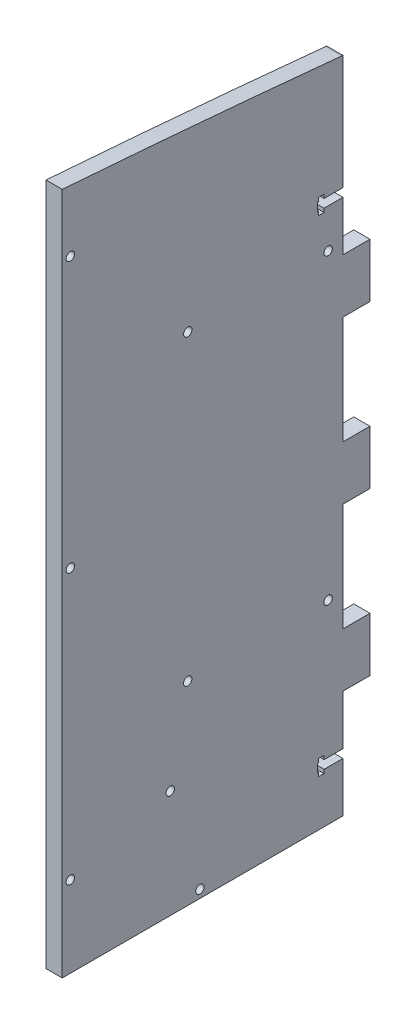
SolidWorks part; units mm, degrees
ref_plane "Płaszczyzna przednia" through (0, 0, 0) normal (0, 0, 1) x (1, 0, 0)
ref_plane "Płaszczyzna górna" through (0, 0, 0) normal (0, 1, 0) x (1, 0, 0)
ref_plane "Płaszczyzna prawa" through (0, 0, 0) normal (1, 0, 0) x (0, 0, -1)
sketch "Szkic1" plane through (0, 0, 0) normal (0, 0, 1) x (1, 0, 0)
  line L0 (-56, -416.604) -> (-50, -416.604)
  line L1 (-56, -416.604) -> (-56, -89.604)
  line L2 (-50, -416.604) -> (-50, -89.604)
  line L3 (-56, -89.604) -> (-50, -89.604)
  line L4 (-56, -416.604) -> (0, -416.604) construction
  dimension "D1" = 6
  dimension "D2" = 327
extrude "Dodanie-wyciągnięcie1" add sketch "Szkic1" along normal blind 108 and the other way blind 6
sketch "Szkic2" plane through (-56, 0, 0) normal (-1, 0, 0) x (0, 0, 1)
  line L0 (-6, -89.604) -> (-6, -416.604) construction
  line L1 (-6, -416.604) -> (4, -416.604)
  line L2 (-6, -416.604) -> (-6, -376.604)
  line L3 (-6, -376.604) -> (4, -376.604)
  line L4 (4, -416.604) -> (4, -376.604)
  line L5 (-6, -356.604) -> (4, -356.604)
  line L6 (-6, -356.604) -> (-6, -316.604)
  line L7 (-6, -316.604) -> (4, -316.604)
  line L8 (4, -356.604) -> (4, -316.604)
  line L9 (4, -176.604) -> (4, -42.6199)
  line L10 (-6, -296.604) -> (4, -296.604)
  line L11 (-6, -296.604) -> (-6, -256.604)
  line L12 (-6, -256.604) -> (4, -256.604)
  line L13 (4, -296.604) -> (4, -256.604)
  line L14 (-6, -236.604) -> (4, -236.604)
  line L15 (-6, -236.604) -> (-6, -196.604)
  line L16 (-6, -176.604) -> (-6, -196.604)
  line L17 (4, -236.604) -> (4, -196.604)
  line L19 (-6, -176.604) -> (-6, -42.6199)
  line L20 (4, -176.604) -> (4, -196.604)
  line L23 (-6, -42.6199) -> (4, -42.6199)
  dimension "D2" = 20
  dimension "D3" = 20
  dimension "D4" = 20
  dimension "D5" = 40
  dimension "D6" = 40
  dimension "D7" = 10
  dimension "D9" = 40
  dimension "D11" = 10
  dimension "D12" = 10
  dimension "D13" = 10
  dimension "D14" = 10
extrude "Wytnij-wyciągnięcie1" cut sketch "Szkic2" against normal blind 6
sketch "Szkic6" plane through (-56, 0, 0) normal (-1, 0, 0) x (0, 0, 1)
  line L2 (58.55, -416.604) -> (58.55, -410.604)
  line L3 (55.45, -416.604) -> (55.45, -410.604)
  line L4 (55.45, -413.604) -> (58.55, -413.604)
  line L5 (58.55, -416.604) -> (58.55, -410.604) construction
  circle A0 centre (57, -413.604) radius 1.55
  dimension "D1" = 3.1
  dimension "D2" = 0
sketch "Szkic7" plane through (-56, 0, 0) normal (-1, 0, 0) x (0, 0, 1)
  circle A0 centre (57, -413.604) radius 1.55 construction
  circle A1 centre (57, -413.604) radius 1.55
extrude "Wytnij-wyciągnięcie2" cut sketch "Szkic7" against normal blind 6
sketch "Szkic8" plane through (-56, 0, 0) normal (-1, 0, 0) x (0, 0, 1)
  line L0 (4, -395.054) -> (11, -395.054)
  line L1 (4, -395.054) -> (4, -398.154)
  line L2 (13.5, -395.054) -> (13.5, -398.154)
  line L3 (4, -398.154) -> (11, -398.154)
  line L4 (4, -416.604) -> (4, -376.604) construction
  line L5 (11, -393.679) -> (13, -393.679)
  line L6 (11, -393.679) -> (11, -395.054)
  line L7 (13, -393.679) -> (13, -395.054)
  line L8 (11, -399.529) -> (13, -399.529)
  line L9 (13, -395.054) -> (13.5, -395.054)
  line L10 (13, -398.154) -> (13, -399.529)
  line L11 (13, -398.154) -> (13.5, -398.154)
  line L12 (11, -398.154) -> (11, -399.529)
  line L13 (4, -376.604) -> (-6, -376.604) construction
  point P14 (4, -396.604)
  dimension "D1" = 9.5
  dimension "D2" = 0.5
  dimension "D3" = 2
  dimension "D4" = 3.1
  dimension "D5" = 1.375
  dimension "D6" = 5.85
  dimension "D7" = 20
extrude "Wytnij-wyciągnięcie3" cut sketch "Szkic8" against normal blind 6
pattern_linear "Szyk liniowy1" count 2 spacing 180 along (0, 1, 0) of "Wytnij-wyciągnięcie3"
sketch "Szkic9" plane through (-56, 0, 0) normal (-1, 0, 0) x (0, 0, 1)
  line L3 (54, -102.604) -> (54, -89.604)
  line L4 (76, -102.604) -> (54, -102.604)
  line L5 (76, -89.604) -> (76, -102.604)
  line L6 (54, -89.604) -> (76, -89.604)
  line L7 (4, -89.604) -> (108, -89.604) construction
  line L8 (4, -215.054) -> (4, -89.604) construction
  dimension "D1" = 13
  dimension "D2" = 0
  dimension "D3" = 22
  dimension "D4" = 50
extrude "Wytnij-wyciągnięcie4" cut sketch "Szkic9" against normal blind 6
sketch "Szkic10" plane through (-56, 0, 0) normal (-1, 0, 0) x (0, 0, 1)
  line L0 (102, -385.054) -> (108, -385.054) construction
  line L1 (102, -388.154) -> (108, -388.154) construction
  line L2 (102, -385.054) -> (108, -385.054)
  line L3 (102, -388.154) -> (108, -388.154)
  line L4 (105, -385.054) -> (105, -388.154)
  circle A1 centre (105, -386.604) radius 1.55
  dimension "D1" = 3.1
sketch "Szkic11" plane through (-56, 0, 0) normal (-1, 0, 0) x (0, 0, 1)
  circle A1 centre (105, -386.604) radius 1.55 construction
  circle A2 centre (105, -386.604) radius 1.55
extrude "Wytnij-wyciągnięcie5" cut sketch "Szkic11" against normal blind 6
pattern_linear "Szyk liniowy2" count 2 spacing 100 along (0, 1, 0) count 2 spacing 200 along (0, 1, 0) of "Wytnij-wyciągnięcie5"
sketch "Szkic14" plane through (-50, 0, 0) normal (1, 0, 0) x (0, 0, -1)
  line L0 (-108, -89.604) -> (-108, -416.604) construction
  line L1 (-4, -416.604) -> (-108, -416.604) construction
  circle A0 centre (-9.5, -232.604) radius 1.55 construction
  circle A1 centre (-61.5, -232.604) radius 1.55 construction
  circle A2 centre (-61.5, -344.604) radius 1.55 construction
  circle A3 centre (-9.5, -344.604) radius 1.55 construction
  circle A4 centre (-68, -376.604) radius 1.55
  circle A5 centre (-9.5, -232.604) radius 1.55
  circle A6 centre (-61.5, -232.604) radius 1.55
  circle A7 centre (-61.5, -344.604) radius 1.55
  circle A8 centre (-9.5, -344.604) radius 1.55
  dimension "D2" = 40
  dimension "D8" = 3.1
  dimension "D16" = 40
extrude "Wytnij-wyciągnięcie7" cut sketch "Szkic14" against normal blind 6
sketch "Szkic15" plane through (-56, 0, 0) normal (-1, 0, 0) x (0, 0, 1)
  line L2 (4, -215.054) -> (4, -89.604) construction
  line L3 (4, -172.6248) -> (4, -89.604)
  line L4 (4.4928, -172.5761) -> (4, -172.6248)
  line L44 (54, -102.604) -> (54, -89.604)
  line L45 (54, -89.604) -> (4, -89.604)
  line L46 (4, -89.604) -> (4, -215.054)
  line L47 (4, -215.054) -> (11, -215.054)
  line L48 (11, -215.054) -> (11, -213.679)
  line L49 (11, -213.679) -> (13, -213.679)
  line L50 (13, -213.679) -> (13, -215.054)
  line L51 (13, -215.054) -> (13.5, -215.054)
  line L52 (13.5, -215.054) -> (13.5, -218.154)
  line L53 (13.5, -218.154) -> (13, -218.154)
  line L54 (13, -218.154) -> (13, -219.529)
  line L55 (13, -219.529) -> (11, -219.529)
  line L56 (11, -219.529) -> (11, -218.154)
  line L57 (11, -218.154) -> (4, -218.154)
  line L58 (4, -218.154) -> (4, -236.604)
  line L59 (4, -236.604) -> (-6, -236.604)
  line L60 (-6, -236.604) -> (-6, -256.604)
  line L61 (-6, -256.604) -> (4, -256.604)
  line L62 (4, -256.604) -> (4, -296.604)
  line L63 (4, -296.604) -> (-6, -296.604)
  line L64 (-6, -296.604) -> (-6, -316.604)
  line L65 (-6, -316.604) -> (4, -316.604)
  line L66 (4, -316.604) -> (4, -356.604)
  line L67 (4, -356.604) -> (-6, -356.604)
  line L68 (-6, -356.604) -> (-6, -376.604)
  line L69 (-6, -376.604) -> (4, -376.604)
  line L70 (4, -376.604) -> (4, -395.054)
  line L71 (4, -395.054) -> (11, -395.054)
  line L72 (11, -395.054) -> (11, -393.679)
  line L73 (11, -393.679) -> (13, -393.679)
  line L74 (13, -393.679) -> (13, -395.054)
  line L75 (13, -395.054) -> (13.5, -395.054)
  line L76 (13.5, -395.054) -> (13.5, -398.154)
  line L77 (13.5, -398.154) -> (13, -398.154)
  line L78 (13, -398.154) -> (13, -399.529)
  line L79 (13, -399.529) -> (11, -399.529)
  line L80 (11, -399.529) -> (11, -398.154)
  line L81 (11, -398.154) -> (4, -398.154)
  line L82 (4, -398.154) -> (4, -416.604)
  line L83 (4, -416.604) -> (108, -416.604)
  line L84 (108, -416.604) -> (108, -89.604)
  line L85 (108, -89.604) -> (76, -89.604)
  line L86 (76, -89.604) -> (76, -102.604)
  line L87 (76, -102.604) -> (54, -102.604)
  line L88 (54, -102.604) -> (54, -89.604)
  line L89 (54, -89.604) -> (4, -89.604)
  line L128 (108, -163.6012) -> (108, -89.604)
  line L129 (108, -89.604) -> (76, -89.604)
  line L130 (76, -89.604) -> (76, -102.604)
  line L131 (76, -102.604) -> (54, -102.604)
  arc A2 (108, -163.6012) -> (4.4928, -172.5761) centre (434.2341, -4527.4043) ccw
  dimension "D1" = 0
extrude "Wytnij-wyciągnięcie9" cut sketch "Szkic15" against normal blind 6
equation "\"tolerancja_wpusy\"=0.2"
equation "\"dlugosc_wpustu_duzy\"=20"
equation "\"srednica_otworu_M3\"=3.1"
equation "\"szerokosc_nogi_T\"=3.1"
equation "\"dlugosc_T_30\"=11"
equation "\"grubosc_na_nakretke_kwadrat\"=2"
equation "\"szerokosc_na_nakretke_kwadrat\"=5.85"
equation "\"wyokosc_nadstawki_T\"=0.5"
equation "\"dlugosc_T_20_6\"=14"
equation "\"D1@Szkic6\"=\"srednica_otworu_M3\""
equation "\"D2@Szkic8\"=\"wyokosc_nadstawki_T\""
equation "\"D3@Szkic8\"=\"grubosc_na_nakretke_kwadrat\""
equation "\"D4@Szkic8\"=\"szerokosc_nogi_T\""
equation "\"D5@Szkic8\"=(\"szerokosc_na_nakretke_kwadrat\"-\"szerokosc_nogi_T\")/2"
equation "\"D6@Szkic8\"=\"szerokosc_na_nakretke_kwadrat\""
equation "\"D8@Szkic14\"=\"srednica_otworu_M3\""
equation "\"D1@Szkic10\" = \"srednica_otworu_M3\""
